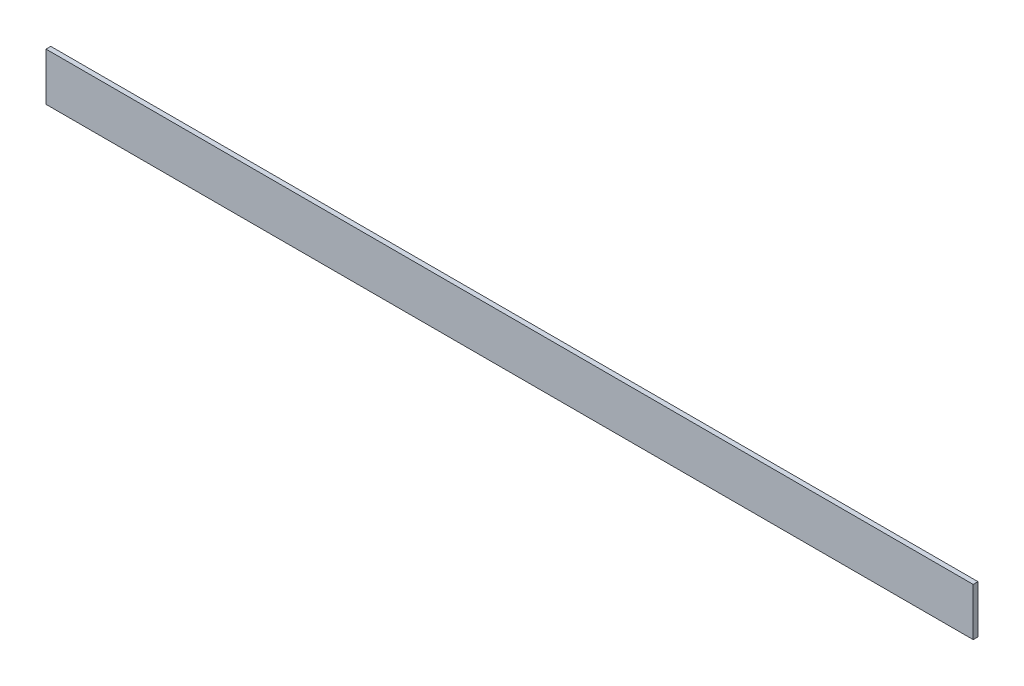
SolidWorks part; units mm, degrees
ref_plane "Front Plane" through (0, 0, 0) normal (0, 0, 1) x (1, 0, 0)
ref_plane "Top Plane" through (0, 0, 0) normal (0, 1, 0) x (1, 0, 0)
ref_plane "Right Plane" through (0, 0, 0) normal (1, 0, 0) x (0, 0, -1)
sketch "Sketch1" plane through (0, 0, 0) normal (0, 0, 1) x (1, 0, 0)
  line L1 (-969, 50) -> (969, 50)
  line L2 (-969, 50) -> (-969, -50)
  line L3 (-969, -50) -> (969, -50)
  line L4 (969, 50) -> (969, -50)
  dimension "D1" = 1938
  dimension "D2" = 100
  dimension "D3" = 50
  dimension "D4" = 969
extrude "Boss-Extrude1" add sketch "Sketch1" along normal blind 10
